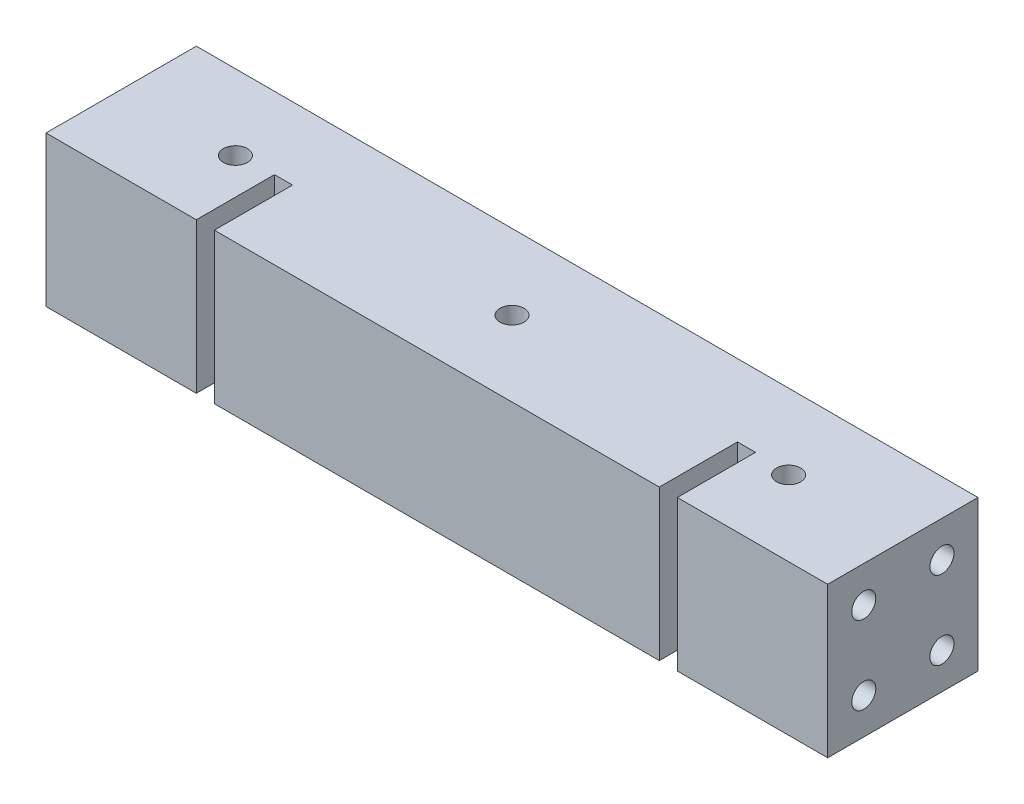
SolidWorks part; units mm, degrees
material "Alumina"
ref_plane "Front Plane" through (0, 0, 0) normal (0, 0, 1) x (1, 0, 0)
ref_plane "Top Plane" through (0, 0, 0) normal (0, 1, 0) x (1, 0, 0)
ref_plane "Right Plane" through (0, 0, 0) normal (1, 0, 0) x (0, 0, -1)
sketch "Sketch1" plane through (0, 0, 0) normal (0, 1, 0) x (1, 0, 0)
  line L0 (0, 0) -> (0, 17210.2354) construction
  line L1 (-65, 12.5) -> (65, 12.5)
  line L2 (-65, 12.5) -> (-65, -12.5)
  line L3 (-65, -12.5) -> (-40, -12.5)
  line L4 (65, 12.5) -> (65, -12.5)
  line L5 (-65, 12.5) -> (65, -12.5) construction
  line L6 (-65, -12.5) -> (65, 12.5) construction
  line L7 (0, 0) -> (17210.2354, 0) construction
  line L8 (-37, -12.5) -> (37, -12.5)
  line L10 (-40, -12.5) -> (-40, 0.5)
  line L11 (-40, 0.5) -> (-37, 0.5)
  line L12 (-37, -12.5) -> (-37, 0.5)
  line L13 (37, -12.5) -> (37, 0.5)
  line L14 (40, 0.5) -> (37, 0.5)
  line L15 (40, -12.5) -> (40, 0.5)
  line L16 (40, -12.5) -> (65, -12.5)
  circle A0 centre (0, 0) radius 2
  circle A1 centre (-46, 0) radius 2
  circle A2 centre (46, 0) radius 2
  point P0 (0, 0)
  dimension "D1" = 4
  dimension "D2" = 130
  dimension "D3" = 25
  dimension "D4" = 46
  dimension "D5" = 13
  dimension "D6" = 3
  dimension "D7" = 37
extrude "Boss-Extrude1" add sketch "Sketch1" along normal mid plane 25 contours L15 L16 L4 L1 L2 L3 L10 L11 L12 L8 L13 L14 A0 A1 A2
sketch "Sketch2" plane through (65, 0, 0) normal (1, 0, 0) x (0, 0, -1)
  line L0 (0, 0) -> (0, 50000) construction
  line L1 (0, 0) -> (-50000, 0) construction
  line L2 (-12.5, 12.5) -> (-12.5, -12.5) construction
  line L3 (12.5, 12.5) -> (-12.5, 12.5) construction
  circle A0 centre (-6.5, 6.5) radius 2
  circle A1 centre (6.5, 6.5) radius 2
  circle A2 centre (6.5, -6.5) radius 2
  circle A3 centre (-6.5, -6.5) radius 2
  dimension "D1" = 4
  dimension "D2" = 6
  dimension "D3" = 6
extrude "Cut-Extrude1" cut sketch "Sketch2" against normal blind 15
cosmetic thread "Cosmetic Thread1" parameters "D2"=5
cosmetic thread "Cosmetic Thread3" parameters "D2"=5
cosmetic thread "Cosmetic Thread5" parameters "D2"=5
cosmetic thread "Cosmetic Thread7" parameters "D2"=5
sketch "Sketch3" plane through (0, 12.5, 0) normal (0, 1, 0) x (1, 0, 0)
  circle A0 centre (46, 0) radius 2 construction
  circle A1 centre (0, 0) radius 2 construction
  circle A2 centre (-46, 0) radius 2 construction
  circle A3 centre (46, 0) radius 2
  circle A4 centre (0, 0) radius 2
  circle A5 centre (-46, 0) radius 2
extrude "Cut-Extrude2" cut sketch "Sketch3" against normal blind 15
cosmetic thread "Cosmetic Thread9" parameters "D2"=5
cosmetic thread "Cosmetic Thread10" parameters "D2"=5
cosmetic thread "Cosmetic Thread11" parameters "D2"=5
mirror "Mirror1" about plane through (0, 0, 0) normal (1, 0, 0) of "Cut-Extrude1"
cosmetic thread "Cosmetic Thread2" parameters "D2"=5
cosmetic thread "Cosmetic Thread4" parameters "D2"=5
cosmetic thread "Cosmetic Thread6" parameters "D2"=5
cosmetic thread "Cosmetic Thread8" parameters "D2"=5
cosmetic thread "Cosmetic Thread12" parameters "D2"=5
cosmetic thread "Cosmetic Thread13" parameters "D2"=5
cosmetic thread "Cosmetic Thread14" parameters "D2"=5
cosmetic thread "Cosmetic Thread15" parameters "D2"=5
